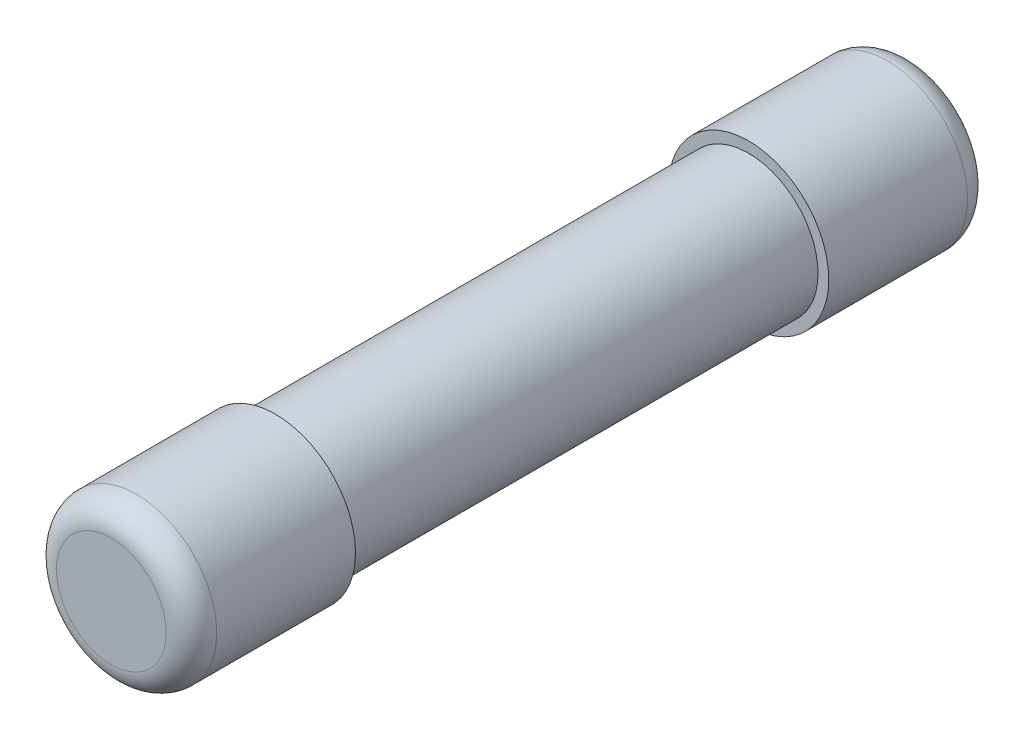
SolidWorks part; units mm, degrees
ref_plane "Front Plane" through (0, 0, 0) normal (0, 0, 1) x (1, 0, 0)
ref_plane "Top Plane" through (0, 0, 0) normal (0, 1, 0) x (1, 0, 0)
ref_plane "Right Plane" through (0, 0, 0) normal (1, 0, 0) x (0, 0, -1)
sketch "Sketch1" plane through (0, 0, 0) normal (1, 0, 0) x (0, 0, -1)
  line L0 (-15.875, 0) -> (15.875, 0) construction
  line L1 (-15.875, -3.175) -> (-15.875, 3.175) construction
  line L2 (15.875, -3.175) -> (15.875, 3.175) construction
  line L3 (0, -2.7495) -> (0, 2.7495) construction
  point P0 (-9.3758, 0)
  point P4 (0, 0)
  point P8 (-15.875, 0)
  point P11 (15.875, 0)
  point P14 (0, 0)
  point P15 (9.3758, 0)
  dimension "Overall Diameter" = 6.35
  dimension "Overall Length" = 31.75
  dimension "D3" = 6.4992
  dimension "D4" = 5.4991
sketch "Sketch3" plane through (0, 0, 0) normal (1, 0, 0) x (0, 0, -1)
  line L0 (-15.875, 0) -> (-14.8439, 0) construction
  line L2 (0, 0) -> (0, 0.6874) construction
  line L3 (-14.8439, 1.7185) -> (14.8439, 1.7185)
  line L4 (-14.8439, 1.7185) -> (-14.8439, 2.7495)
  line L5 (-14.8439, 2.7495) -> (14.8439, 2.7495)
  line L6 (14.8439, 1.7185) -> (14.8439, 2.7495)
  line L7 (0, -2.7495) -> (0, 2.7495) construction
  line L8 (0, 0.6874) -> (0, 1.3748) construction
  line L9 (0, 1.3748) -> (0, 2.0622) construction
  line L10 (0, 2.0622) -> (0, 2.7495) construction
  line L11 (-15.875, 0) -> (15.875, 0) construction
  point P10 (0, 1.7185)
revolve "Revolve1" add sketch "Sketch3" angle 360 about L0
sketch "Sketch4" plane through (0, 0, 0) normal (1, 0, 0) x (0, 0, -1)
  line L0 (-9.3758, 2.7495) -> (-9.3758, 3.175)
  line L1 (14.8439, 2.7495) -> (-14.8439, 2.7495) construction
  line L2 (-9.3758, 3.175) -> (-15.875, 3.175)
  line L3 (-15.875, 3.175) -> (-15.875, 0)
  line L4 (-15.875, 0) -> (-14.8439, 0)
  line L5 (-15.875, 0) -> (15.875, 0) construction
  line L6 (-14.8439, 0) -> (-14.8439, 2.7495)
  line L7 (-14.8439, 2.7495) -> (-9.3758, 2.7495)
revolve "Revolve2" add sketch "Sketch4" angle 360 about L4
fillet "Fillet1" radius 1 1 edges at (3.175, 0, 15.875)
mirror "Mirror1" about plane through (0, 0, 0) normal (0, 0, 1) of bodies 105
equation "\"D4@Sketch1\" = \"Overall Diameter@Sketch1\" * .866"
equation "\"D3@Sketch1\" = \"Overall Length@Sketch1\" * .2047"
